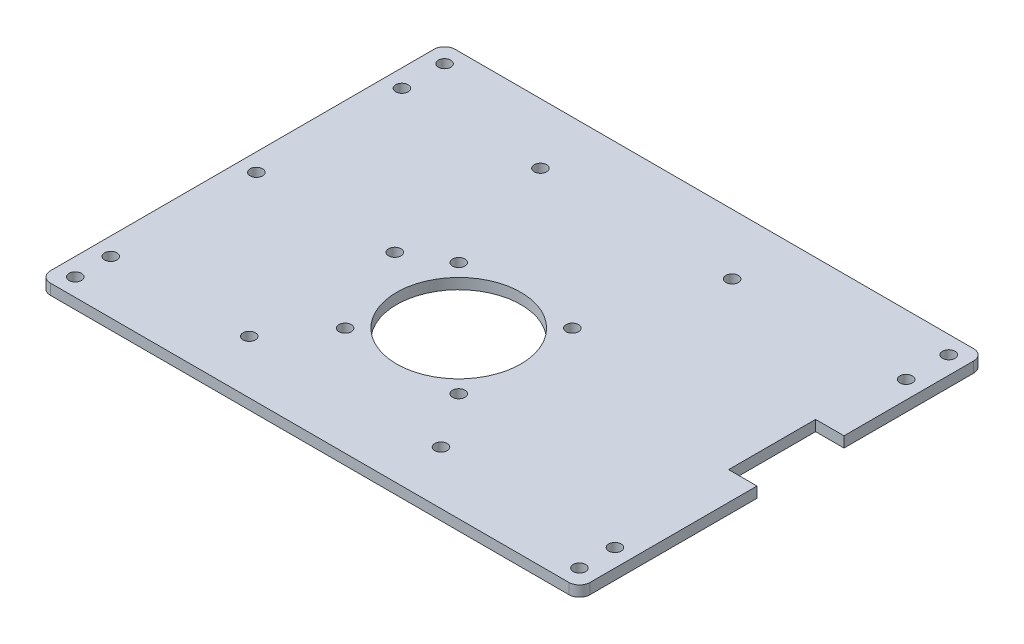
SolidWorks part; units mm, degrees
ref_plane "前视基准面" through (0, 0, 0) normal (0, 0, 1) x (1, 0, 0)
ref_plane "上视基准面" through (0, 0, 0) normal (0, 1, 0) x (1, 0, 0)
ref_plane "右视基准面" through (0, 0, 0) normal (1, 0, 0) x (0, 0, -1)
sketch "草图1" plane through (0, 0, 0) normal (0, 1, 0) x (1, 0, 0)
  line L0 (76, 17.5) -> (68, 17.5)
  line L1 (-73, 57) -> (73, 57)
  line L2 (-76, 54) -> (-76, -54)
  line L3 (-73, -57) -> (73, -57)
  line L4 (76, 54) -> (76, 17.5)
  line L5 (-76, 57) -> (76, -57) construction
  line L6 (-76, -57) -> (76, 57) construction
  line L7 (68, 17.5) -> (68, -7)
  line L8 (68, -7) -> (76, -7)
  line L9 (76, -7) -> (76, -54)
  line L10 (0, 57) -> (0, -57) construction
  arc A0 (-76, 54) -> (-73, 57) centre (-73, 54) cw
  arc A1 (76, 54) -> (73, 57) centre (73, 54) ccw
  arc A2 (76, -54) -> (73, -57) centre (73, -54) cw
  arc A3 (-73, -57) -> (-76, -54) centre (-73, -54) cw
  circle A4 centre (-71, 52) radius 1.75
  circle A5 centre (71, 52) radius 1.75
  circle A6 centre (71, -52) radius 1.75
  circle A7 centre (-71, -52) radius 1.75
  circle A8 centre (-4.5, -10.5) radius 17.5
  circle A9 centre (-20.5, 5.5) radius 1.75
  circle A10 centre (11.5, 5.5) radius 1.75
  circle A11 centre (11.5, -26.5) radius 1.75
  circle A12 centre (-20.5, -26.5) radius 1.75
  circle A13 centre (71, 40) radius 1.75
  circle A14 centre (22, 40) radius 1.75
  circle A15 centre (22, -42) radius 1.75
  circle A16 centre (71, -42) radius 1.75
  circle A18 centre (-71, 40) radius 1.75
  circle A19 centre (-32, 40) radius 1.75
  circle A20 centre (-32, -1) radius 1.75
  circle A21 centre (-32, -42) radius 1.75
  circle A22 centre (-71, -1) radius 1.75
  circle A23 centre (-71, -42) radius 1.75
  point P0 (0, 0)
  point P28 (-4.5, -10.5)
  dimension "D3" = 3
  dimension "D4" = 3
  dimension "D5" = 3
  dimension "D6" = 3
  dimension "D7" = 71
  dimension "D16" = 16
  dimension "D20" = 40
  dimension "D1" = 114
  dimension "D2" = 152
  dimension "D8" = 52
  dimension "D11" = 39.5
  dimension "D12" = 8
  dimension "D13" = 24.5
  dimension "D14" = 71.5
  dimension "D15" = 46.5
  dimension "D17" = 16
  dimension "D9" = 2
  dimension "D10" = 2
  dimension "D18" = 2
  dimension "D19" = 2
  dimension "D21" = 2
  dimension "D22" = 2
  dimension "D23" = 2
  dimension "D24" = 3
extrude "凸台-拉伸1" add sketch "草图1" along normal blind 3
